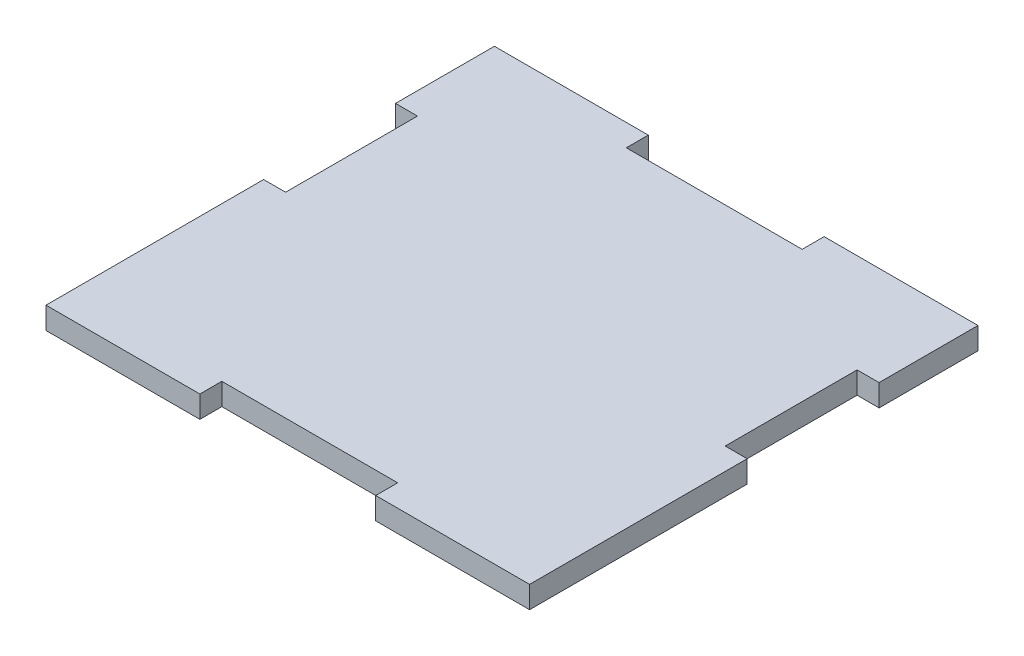
SolidWorks part; units mm, degrees
ref_plane "前视基准面" through (0, 0, 0) normal (0, 0, 1) x (1, 0, 0)
ref_plane "上视基准面" through (0, 0, 0) normal (0, 1, 0) x (1, 0, 0)
ref_plane "右视基准面" through (0, 0, 0) normal (1, 0, 0) x (0, 0, -1)
sketch "草图1" plane through (0, 0, 0) normal (0, 1, 0) x (1, 0, 0)
  line L0 (75, 102) -> (110, 102)
  line L1 (0, 0) -> (35, 0)
  line L2 (0, 0) -> (0, 49.5)
  line L3 (0, 102) -> (35, 102)
  line L4 (110, 0) -> (110, 49.5)
  line L6 (35, 102) -> (35, 97)
  line L7 (35, 97) -> (75, 97)
  line L8 (75, 102) -> (75, 97)
  line L10 (35, 0) -> (35, 5)
  line L11 (35, 5) -> (75, 5)
  line L12 (75, 0) -> (75, 5)
  line L13 (0, 79.5) -> (5, 79.5)
  line L15 (0, 49.5) -> (5, 49.5)
  line L16 (5, 79.5) -> (5, 49.5)
  line L17 (110, 79.5) -> (105, 79.5)
  line L19 (110, 49.5) -> (105, 49.5)
  line L20 (105, 79.5) -> (105, 49.5)
  line L21 (110, 79.5) -> (110, 102)
  line L22 (0, 79.5) -> (0, 102)
  line L23 (75, 0) -> (110, 0)
  point P13 (75, 99.5)
  dimension "D1" = 110
  dimension "D2" = 102
  dimension "D3" = 40
  dimension "D4" = 5
  dimension "D5" = 40
  dimension "D6" = 5
  dimension "D7" = 35
  dimension "D8" = 35
  dimension "D9" = 30
  dimension "D10" = 5
  dimension "D11" = 5
  dimension "D12" = 30
  dimension "D13" = 22.5
  dimension "D14" = 22.5
extrude "凸台-拉伸1" add sketch "草图1" along normal blind 5
